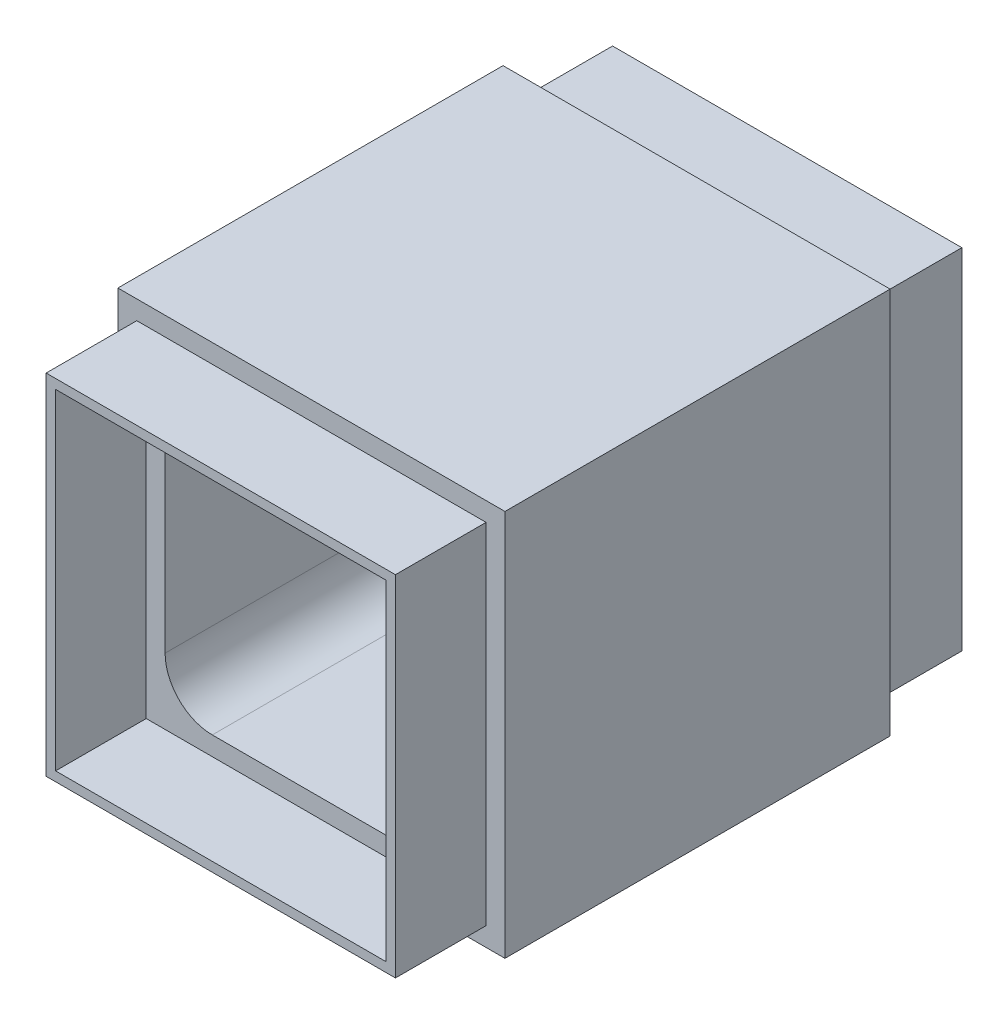
SolidWorks part; units mm, degrees
ref_plane "Front Plane" through (0, 0, 0) normal (0, 0, 1) x (1, 0, 0)
ref_plane "Top Plane" through (0, 0, 0) normal (0, 1, 0) x (1, 0, 0)
ref_plane "Right Plane" through (0, 0, 0) normal (1, 0, 0) x (0, 0, -1)
sketch "Sketch1" plane through (0, 0, 0) normal (0, 0, 1) x (1, 0, 0)
  line L1 (0, 0) -> (52.07, 0)
  line L2 (0, 0) -> (0, 52.07)
  line L3 (0, 52.07) -> (52.07, 52.07)
  line L4 (52.07, 0) -> (52.07, 52.07)
  dimension "D1" = 52.07
  dimension "D2" = 52.07
extrude "Boss-Extrude1" add sketch "Sketch1" against normal blind 76.2
sketch "Sketch2" plane through (0, 0, 0) normal (0, 0, 1) x (1, 0, 0)
  line L0 (0, 52.07) -> (0, 0) construction
  line L1 (6.35, 45.72) -> (45.72, 45.72)
  line L2 (6.35, 45.72) -> (6.35, 6.35)
  line L3 (6.35, 6.35) -> (45.72, 6.35)
  line L4 (45.72, 45.72) -> (45.72, 6.35)
  line L5 (0, 0) -> (52.07, 0) construction
  line L6 (52.07, 0) -> (52.07, 52.07) construction
  line L7 (52.07, 52.07) -> (0, 52.07) construction
  dimension "D1" = 6.35
  dimension "D2" = 6.35
  dimension "D3" = 6.35
  dimension "D4" = 6.35
extrude "Cut-Extrude1" cut sketch "Sketch2" against normal through all
sketch "Sketch3" plane through (0, 0, 0) normal (0, 0, 1) x (1, 0, 0)
  line L0 (0, 52.07) -> (0, 0) construction
  line L1 (2.54, 49.53) -> (49.53, 49.53)
  line L2 (2.54, 49.53) -> (2.54, 2.54)
  line L3 (2.54, 2.54) -> (49.53, 2.54)
  line L4 (49.53, 49.53) -> (49.53, 2.54)
  line L5 (52.07, 0) -> (52.07, 52.07) construction
  line L6 (0, 0) -> (52.07, 0) construction
  line L7 (52.07, 52.07) -> (0, 52.07) construction
  line L9 (3.81, 48.26) -> (48.26, 48.26)
  line L10 (3.81, 48.26) -> (3.81, 3.81)
  line L11 (3.81, 3.81) -> (48.26, 3.81)
  line L12 (48.26, 48.26) -> (48.26, 3.81)
  line M9 (45.72, 6.35) -> (6.35, 6.35)
  line M10 (6.35, 6.35) -> (6.35, 45.72)
  line M11 (6.35, 45.72) -> (45.72, 45.72)
  line M12 (45.72, 45.72) -> (45.72, 6.35)
  line M13 (0, 52.07) -> (0, 0)
  line M14 (0, 0) -> (52.07, 0)
  line M15 (52.07, 0) -> (52.07, 52.07)
  line M16 (52.07, 52.07) -> (0, 52.07)
  dimension "D1" = 2.54
  dimension "D2" = 2.54
  dimension "D3" = 2.54
  dimension "D4" = 2.54
  dimension "D5" = 1.27
  dimension "D6" = 1.27
  dimension "D7" = 1.27
  dimension "D8" = 1.27
extrude "Cut-Extrude2" cut sketch "Sketch3" against normal blind 12.192 contours L1 L4 L3 L2 M16 M13 M14 M15 | L12 L9 L10 L11 M12 M9 M10 M11
ref_plane "Plane1" through (0, 0, -38.1) normal (0, 0, -1) x (-1, 0, 0)
mirror "Mirror1" about plane through (0, 0, -38.1) normal (0, 0, -1) of "Cut-Extrude2"
fillet "Fillet1" radius 6.35 4 edges at (6.35, 45.72, -38.1) (45.72, 45.72, -38.1) (45.72, 6.35, -38.1) (6.35, 6.35, -38.1)
